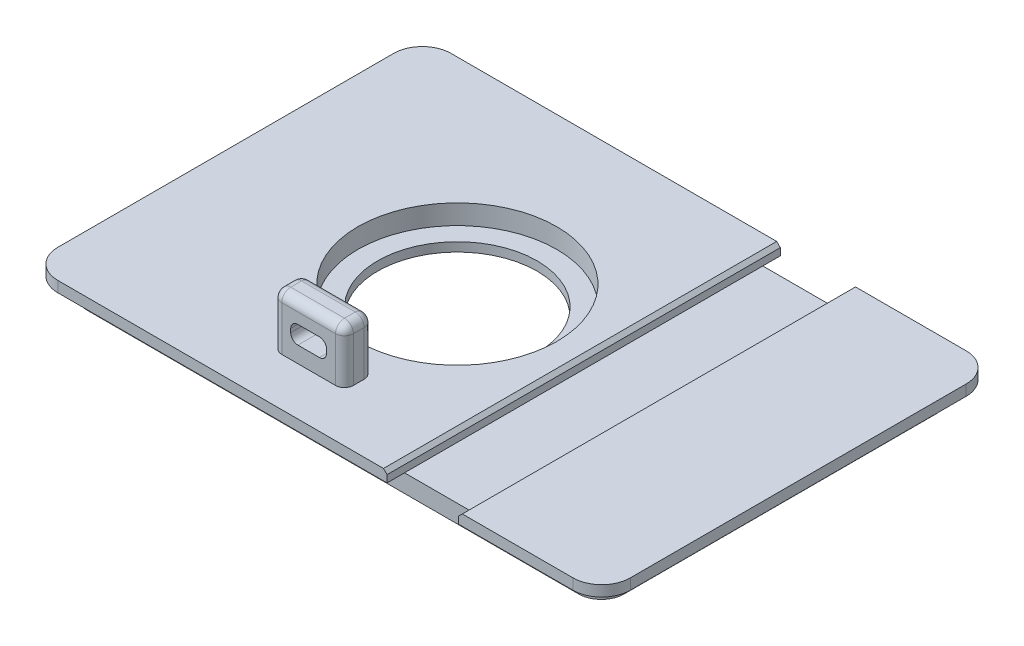
SolidWorks part; units mm, degrees
material "ABS"
ref_plane "Front Plane" through (0, 0, 0) normal (0, 0, 1) x (1, 0, 0)
ref_plane "Top Plane" through (0, 0, 0) normal (0, 1, 0) x (1, 0, 0)
ref_plane "Right Plane" through (0, 0, 0) normal (1, 0, 0) x (0, 0, -1)
sketch "Sketch1" plane through (0, 0, 0) normal (0, 1, 0) x (1, 0, 0)
  line L0 (79.883, 54.864) -> (-79.883, -54.864) construction
  line L1 (-71.882, 54.864) -> (71.882, 54.864)
  line L2 (-79.883, 46.863) -> (-79.883, -46.863)
  line L3 (-71.882, -54.864) -> (71.882, -54.864)
  line L4 (79.883, 46.863) -> (79.883, -46.863)
  arc A0 (-79.883, -46.863) -> (-71.882, -54.864) centre (-71.882, -46.863) ccw
  arc A1 (-71.882, 54.864) -> (-79.883, 46.863) centre (-71.882, 46.863) ccw
  arc A2 (71.882, 54.864) -> (79.883, 46.863) centre (71.882, 46.863) cw
  arc A3 (71.882, -54.864) -> (79.883, -46.863) centre (71.882, -46.863) ccw
  point P4 (0, 0)
  point P11 (-79.883, 54.864)
  point P17 (79.883, -54.864)
  point P18 (75.819, 50.8)
  point P19 (75.819, -50.8)
  point P20 (-75.819, -50.8)
  point P21 (-75.819, 50.8)
  dimension "D3" = 8.001
  dimension "D1" = 159.766
  dimension "D2" = 109.728
extrude "Extrude1" add sketch "Sketch1" along normal blind 2.9972
sketch "Sketch2" plane through (0, 0, 0) normal (0, -1, 0) x (1, 0, 0)
  line L1 (68.58, -49.9872) -> (-68.58, -49.9872)
  line L2 (74.93, -43.6372) -> (74.93, 43.6372)
  line L3 (68.58, 49.9872) -> (-68.58, 49.9872)
  line L4 (-74.93, -43.6372) -> (-74.93, 43.6372)
  line L5 (74.93, -49.9872) -> (-74.93, 49.9872) construction
  line L6 (74.93, 49.9872) -> (-74.93, -49.9872) construction
  arc A0 (74.93, 43.6372) -> (68.58, 49.9872) centre (68.58, 43.6372) ccw
  arc A1 (-68.58, 49.9872) -> (-74.93, 43.6372) centre (-68.58, 43.6372) ccw
  arc A2 (-68.58, -49.9872) -> (-74.93, -43.6372) centre (-68.58, -43.6372) cw
  arc A3 (68.58, -49.9872) -> (74.93, -43.6372) centre (68.58, -43.6372) ccw
  point P0 (0, 0)
  dimension "D3" = 6.35
  dimension "D1" = 99.9744
  dimension "D2" = 149.86
extrude "Extrude2" add sketch "Sketch2" along normal blind 5.0038
sketch "Sketch3" plane through (0, 2.9972, 0) normal (0, 1, 0) x (1, 0, 0)
  line L0 (-4.4005, 0) -> (4.4005, 0) construction
  circle A0 centre (-15.25, 0) radius 27.75
  dimension "D1" = 55.5
  dimension "D2" = 15.25
extrude "Extrude3" cut sketch "Sketch3" against normal blind 5.5
sketch "Sketch5" plane through (0, -2.5028, 0) normal (0, 1, 0) x (1, 0, 0)
  circle A3 centre (-15.25, 0) radius 22.25
extrude "Extrude4" cut sketch "Sketch5" against normal through all
sketch "Sketch6" plane through (0, 0, 0) normal (0, 0, 1) x (1, 0, 0)
  line L0 (20, 0) -> (20, 3)
  line L1 (20, 3) -> (40, 3)
  line L2 (40, 3) -> (40, 0)
  line L3 (40, 0) -> (20, 0)
extrude "Cut-Extrude1" cut sketch "Sketch6" against normal blind 60 and the other way blind 60
chamfer "Chamfer1" distance 1 angle 45 2 edges at (40, 2.9972, 0) (20, 2.9972, 0)
sketch "Sketch7" plane through (0, 2.9972, 0) normal (0, 1, 0) x (1, 0, 0)
  line L2 (-5.25, -41.5) -> (-25.25, -41.5)
  line L3 (-5.25, -41.5) -> (-5.25, -33.5)
  line L4 (-5.25, -33.5) -> (-25.25, -33.5)
  line L5 (-25.25, -41.5) -> (-25.25, -33.5)
  line L6 (-5.25, -41.5) -> (-25.25, -33.5) construction
  line L7 (-5.25, -33.5) -> (-25.25, -41.5) construction
  point P3 (-15.25, -37.5)
extrude "Boss-Extrude1" add sketch "Sketch7" along normal blind 15
fillet "Fillet1" radius 2.5 8 edges at (-5.25, 17.9972, 37.5) (-15.25, 17.9972, 41.5) (-25.25, 17.9972, 37.5) (-25.25, 10.4972, 41.5) (-5.25, 10.4972, 41.5) (-15.25, 17.9972, 33.5) (-25.25, 10.4972, 33.5) (-5.25, 10.4972, 33.5)
sketch "Sketch8" plane through (0, 0, 33.5) normal (0, 0, -1) x (-1, 0, 0)
  line L1 (12.25, 12.5) -> (18.25, 12.5)
  line L2 (10.25, 10.5) -> (10.25, 9.5)
  line L3 (12.25, 7.5) -> (18.25, 7.5)
  line L4 (20.25, 10.5) -> (20.25, 9.5)
  line L5 (10.25, 12.5) -> (20.25, 7.5) construction
  line L6 (10.25, 7.5) -> (20.25, 12.5) construction
  arc A0 (18.25, 12.5) -> (20.25, 10.5) centre (18.25, 10.5) cw
  arc A1 (18.25, 7.5) -> (20.25, 9.5) centre (18.25, 9.5) ccw
  arc A2 (10.25, 9.5) -> (12.25, 7.5) centre (12.25, 9.5) ccw
  arc A3 (12.25, 12.5) -> (10.25, 10.5) centre (12.25, 10.5) ccw
  point P0 (15.25, 10)
  dimension "D1" = 2
extrude "Cut-Extrude2" cut sketch "Sketch8" against normal blind 15
